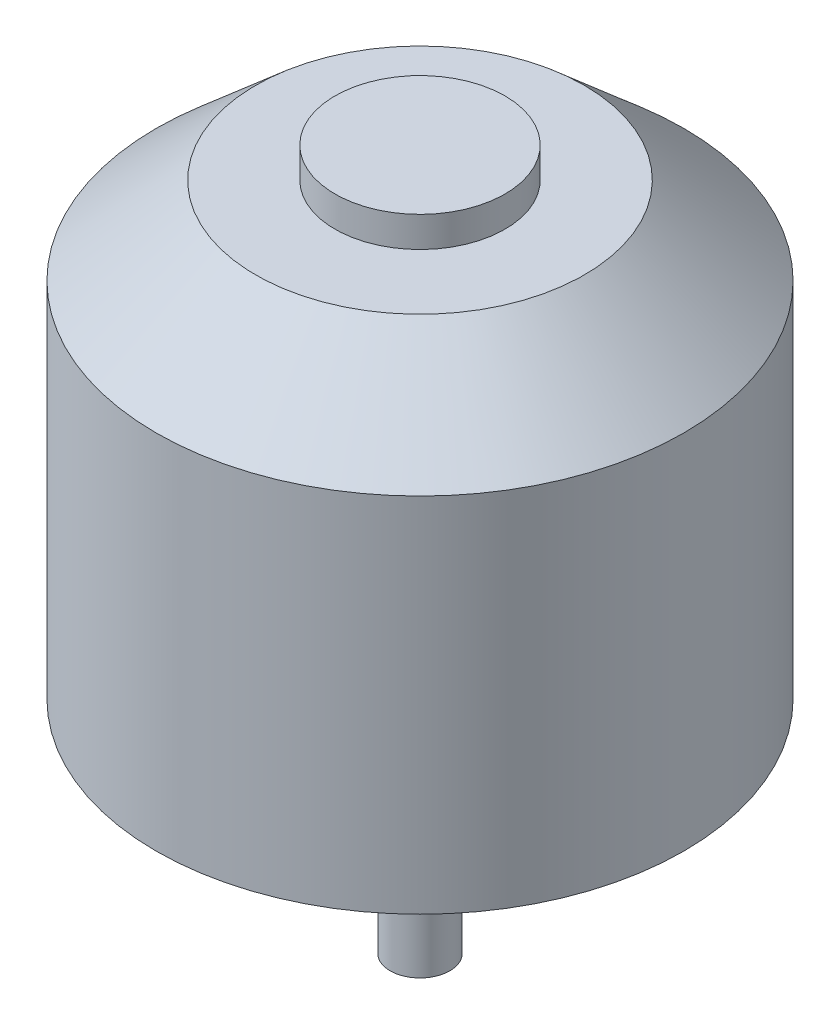
SolidWorks part; units mm, degrees
ref_plane "Front Plane" through (0, 0, 0) normal (0, 0, 1) x (1, 0, 0)
ref_plane "Top Plane" through (0, 0, 0) normal (0, 1, 0) x (1, 0, 0)
ref_plane "Right Plane" through (0, 0, 0) normal (1, 0, 0) x (0, 0, -1)
sketch "Sketch1" plane through (0, 0, 0) normal (0, 0, 1) x (1, 0, 0)
  line L0 (0, 0) -> (0, 25.4) construction
  line L1 (0, 0) -> (13.97, 0)
  line L2 (13.97, 0) -> (13.97, 19.177)
  line L3 (13.97, 19.177) -> (8.6995, 23.7871)
  line L4 (8.6995, 23.7871) -> (4.5022, 23.7871)
  line L5 (4.5022, 23.7871) -> (4.5022, 25.4)
  line L6 (4.5022, 25.4) -> (0, 25.4)
  line L7 (0, 25.4) -> (0, 0)
  dimension "D1" = 25.4
  dimension "D2" = 4.5022
  dimension "D3" = 19.177
  dimension "D4" = 1.6129
  dimension "D5" = 8.6995
  dimension "D6" = 13.97
revolve "Revolve1" add sketch "Sketch1" angle 360 about L0
sketch "Sketch2" plane through (0, 0, 0) normal (0, -1, 0) x (1, 0, 0)
  circle A0 centre (0, 0) radius 1.58
  dimension "D1" = 3.16
extrude "Boss-Extrude1" add sketch "Sketch2" along normal blind 11.684
hole_wizard "M3x0.5 Bottoming Tapped Hole1" positions "Sketch4" profile "Sketch3" tap size "M3x0.5" standard "HASCO Metric"
sketch "Sketch4" plane through (0, 0, 0) normal (0, -1, 0) x (-1, 0, 0)
  circle A0 centre (0, 0) radius 1.58 construction
  circle A1 centre (0, 0) radius 1.58 construction
  point P0 (-8, 0)
  point P2 (8, 0)
  point P4 (0, -9.5)
  point P6 (0, 9.5)
  dimension "D2" = 9.5
  dimension "D4" = 8
  dimension "D1" = 19
  dimension "D3" = 16
sketch "Sketch3" plane through (8, 0, 0) normal (1, 0, 0) x (0, 0, -1)
  line L0 (0, 0) -> (0, 3.9261)
  line L1 (0, 3.9261) -> (1.25, 3.175)
  line L2 (1.25, 3.175) -> (1.25, 0)
  line L5 (1.25, 0) -> (0, 0)
  line L10 (0, 3.9261) -> (-1.25, 3.175) construction
  line L11 (0, -6.35) -> (0, 107.95) construction
  dimension "Tap Drill Dia." = 2.5
  dimension "Tap Drill Depth" = 3.175
  dimension "Drill Angle" = 118
